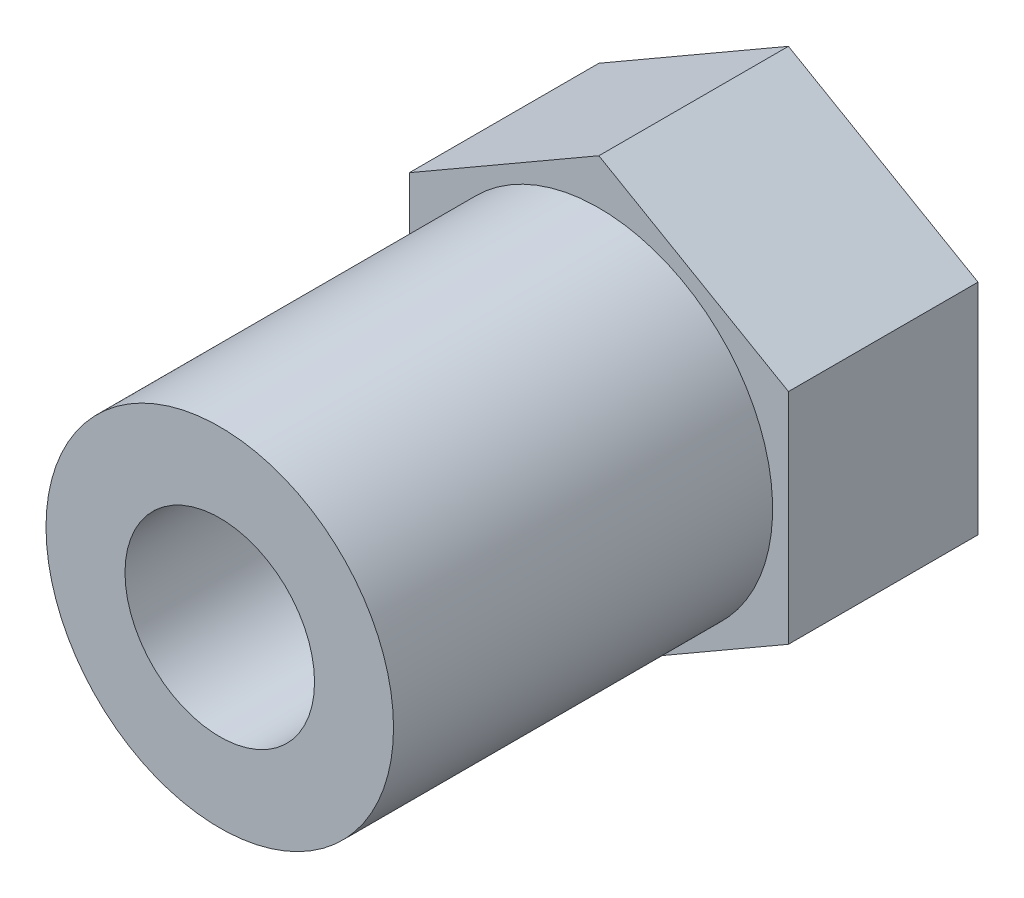
SolidWorks part; units mm, degrees
ref_plane "Alzado" through (0, 0, 0) normal (0, 0, 1) x (1, 0, 0)
ref_plane "Planta" through (0, 0, 0) normal (0, 1, 0) x (1, 0, 0)
ref_plane "Vista lateral" through (0, 0, 0) normal (1, 0, 0) x (0, 0, -1)
sketch "Croquis2" plane through (0, 0, 0) normal (0, 0, 1) x (1, 0, 0)
  line L0 (0, 13.162) -> (0, -15.8742) construction
  line L1 (-13.0025, 0) -> (13.0025, 0) construction
  circle A0 centre (0, 0) radius 5.5
  point P7 (0, 0)
  point P8 (5.7434, 0)
  dimension "D1" = 11
extrude "Saliente-Extruir1" add sketch "Croquis2" along normal blind 18
sketch "Croquis3" plane through (0, 0, 0) normal (0, 0, -1) x (-1, 0, 0)
  line L0 (0, 6.2642) -> (0, -7.7284) construction
  line L1 (-7.1186, 0) -> (8.1779, 0) construction
  line L3 (0, 6.9282) -> (-6, 3.4641)
  line L4 (-6, 3.4641) -> (-6, -3.4641)
  line L5 (-6, -3.4641) -> (0, -6.9282)
  line L6 (0, -6.9282) -> (6, -3.4641)
  line L7 (6, -3.4641) -> (6, 3.4641)
  line L8 (6, 3.4641) -> (0, 6.9282)
  circle A0 centre (0, 0) radius 6 construction
  dimension "D1" = 12
extrude "Saliente-Extruir2" add sketch "Croquis3" against normal blind 6
sketch "Croquis4" plane through (0, 0, 18) normal (0, 0, 1) x (1, 0, 0)
  line L0 (0, 6.443) -> (0, -6.4131) construction
  line L1 (-7.3975, 0) -> (8.0835, 0) construction
  circle A0 centre (0, 0) radius 3
  dimension "D1" = 6
extrude "Cortar-Extruir1" cut sketch "Croquis4" against normal blind 12
sketch "Croquis5" plane through (0, 0, 0) normal (0, 0, -1) x (-1, 0, 0)
  line L0 (0, 8.8347) -> (0, -7.3217) construction
  line L1 (-7.1124, 0) -> (8.4404, 0) construction
  circle A0 centre (0, 0) radius 1.5
  dimension "D1" = 3
extrude "Cortar-Extruir2" cut sketch "Croquis5" against normal blind 6
